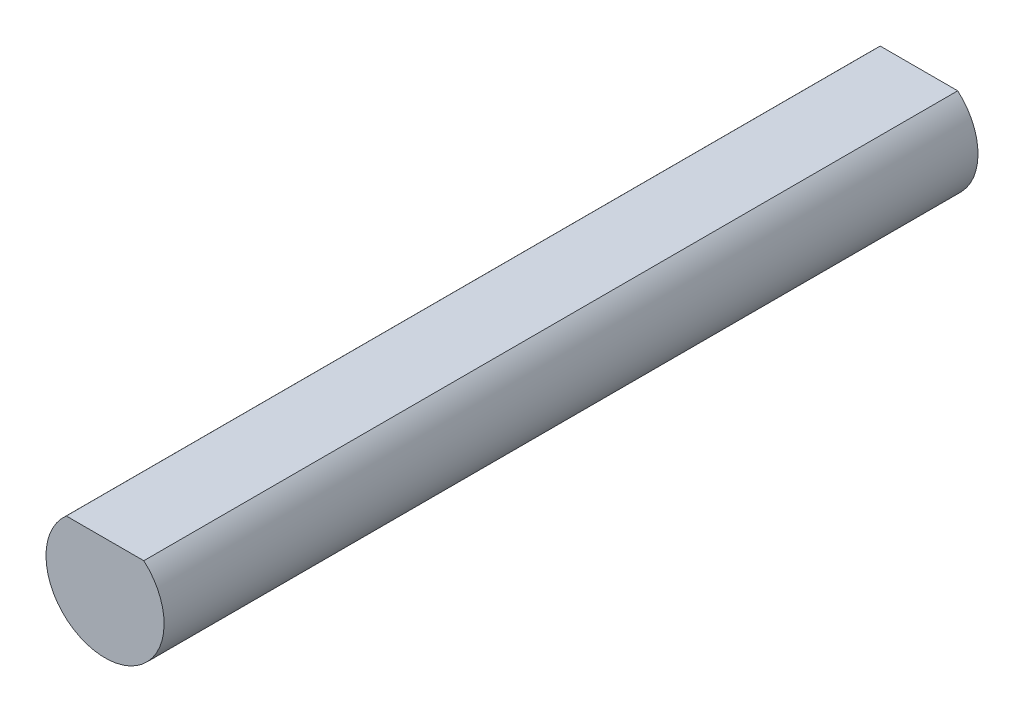
SolidWorks part; units mm, degrees
ref_plane "Front Plane" through (0, 0, 0) normal (0, 0, 1) x (1, 0, 0)
ref_plane "Top Plane" through (0, 0, 0) normal (0, 1, 0) x (1, 0, 0)
ref_plane "Right Plane" through (0, 0, 0) normal (1, 0, 0) x (0, 0, -1)
sketch "Sketch1" plane through (0, 0, 0) normal (0, 0, 1) x (1, 0, 0)
  line L0 (-2.6192, 3.01) -> (2.6192, 3.01)
  arc A0 (-2.6192, 3.01) -> (2.6192, 3.01) centre (0, 0) ccw
  arc A1 (2.6192, 3.01) -> (-2.6192, 3.01) centre (0, 0) ccw construction
  point P5 (0, -3.99)
  dimension "D1" = 7.98
  dimension "D2" = 7
extrude "Boss-Extrude1" add sketch "Sketch1" along normal mid plane 55
